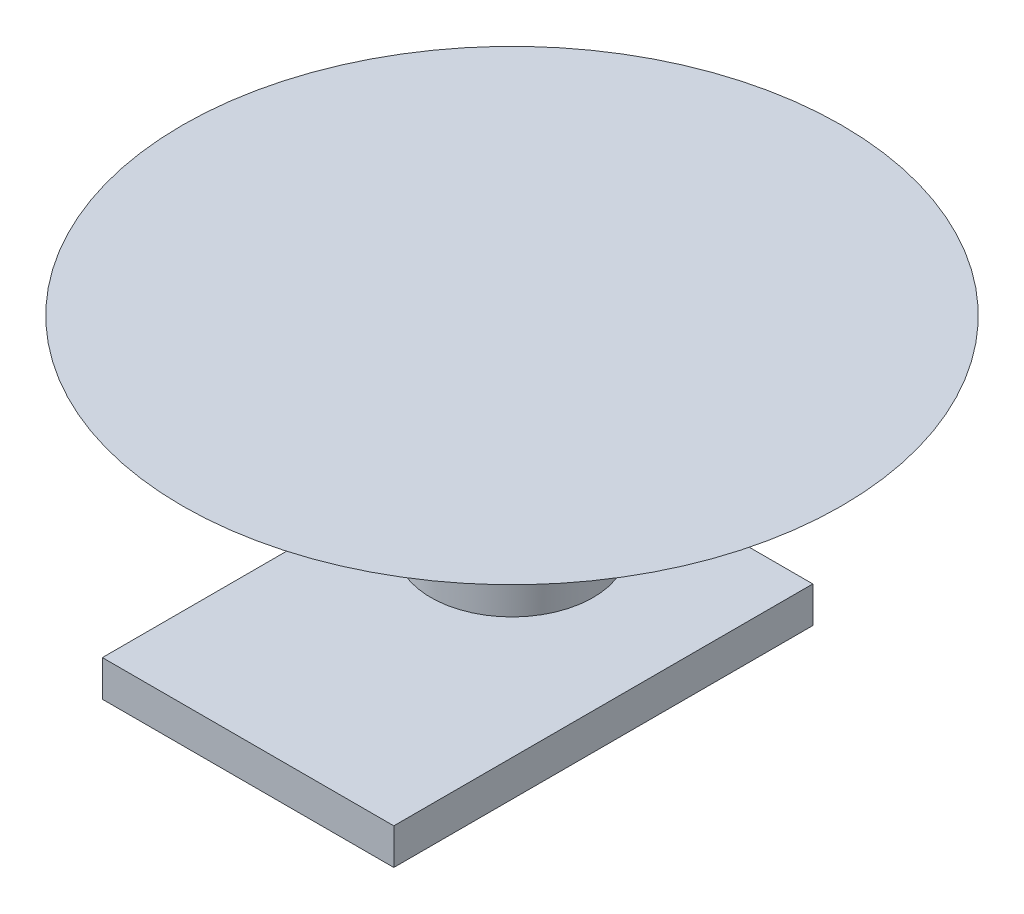
SolidWorks part; units mm, degrees
ref_plane "Front Plane" through (0, 0, 0) normal (0, 0, 1) x (1, 0, 0)
ref_plane "Top Plane" through (0, 0, 0) normal (0, 1, 0) x (1, 0, 0)
ref_plane "Right Plane" through (0, 0, 0) normal (1, 0, 0) x (0, 0, -1)
sketch "Sketch1" plane through (0, 0, 0) normal (0, 1, 0) x (1, 0, 0)
  line L1 (-20.5105, -29.4894) -> (20.5105, -29.4894)
  line L2 (-20.5105, -29.4894) -> (-20.5105, 29.4894)
  line L3 (-20.5105, 29.4894) -> (20.5105, 29.4894)
  line L4 (20.5105, -29.4894) -> (20.5105, 29.4894)
  line L5 (-20.5105, -29.4894) -> (20.5105, 29.4894) construction
  line L6 (-20.5105, 29.4894) -> (20.5105, -29.4894) construction
  point P0 (0, 0)
  dimension "D1" = 41.021
  dimension "D2" = 58.9788
extrude "Boss-Extrude1" add sketch "Sketch1" along normal blind 5.08
sketch "Sketch2" plane through (0, 5.08, 0) normal (0, 1, 0) x (1, 0, 0)
  line L0 (20.5105, 29.4894) -> (-20.5105, 29.4894) construction
  line L1 (-20.5105, 29.4894) -> (-20.5105, -29.4894) construction
  circle A0 centre (-4.7117, 12.3698) radius 11.43
  dimension "D1" = 22.86
  dimension "D2" = 17.1196
  dimension "D3" = 15.7988
extrude "Boss-Extrude2" add sketch "Sketch2" along normal blind 8.001
sketch "Sketch3" plane through (0, 13.081, 0) normal (0, 1, 0) x (1, 0, 0)
  circle A0 centre (-4.7117, 12.3698) radius 11.43 construction
  point P0 (-4.7117, 23.7998)
  point P1 (-4.7117, 0.9398)
ref_plane "Plane1" through (-4.7117, 0, 0) normal (1, 0, 0) x (0, 0, -1)
sketch "Sketch5" plane through (0, 13.081, 0) normal (0, 1, 0) x (1, 0, 0)
  point P0 (-4.7117, 12.3698)
sketch "Sketch6" plane through (-4.7117, 0, 0) normal (1, 0, 0) x (0, 0, -1)
  line L0 (12.3698, 13.081) -> (58.7779, 33.7432)
  line L1 (58.7779, 33.7432) -> (12.3698, 33.7432)
  line L2 (12.3698, 33.7432) -> (12.3698, 13.081)
  dimension "D1" = 66
  dimension "D2" = 50.8
revolve "Revolve1" add sketch "Sketch6" angle 360 about L2
